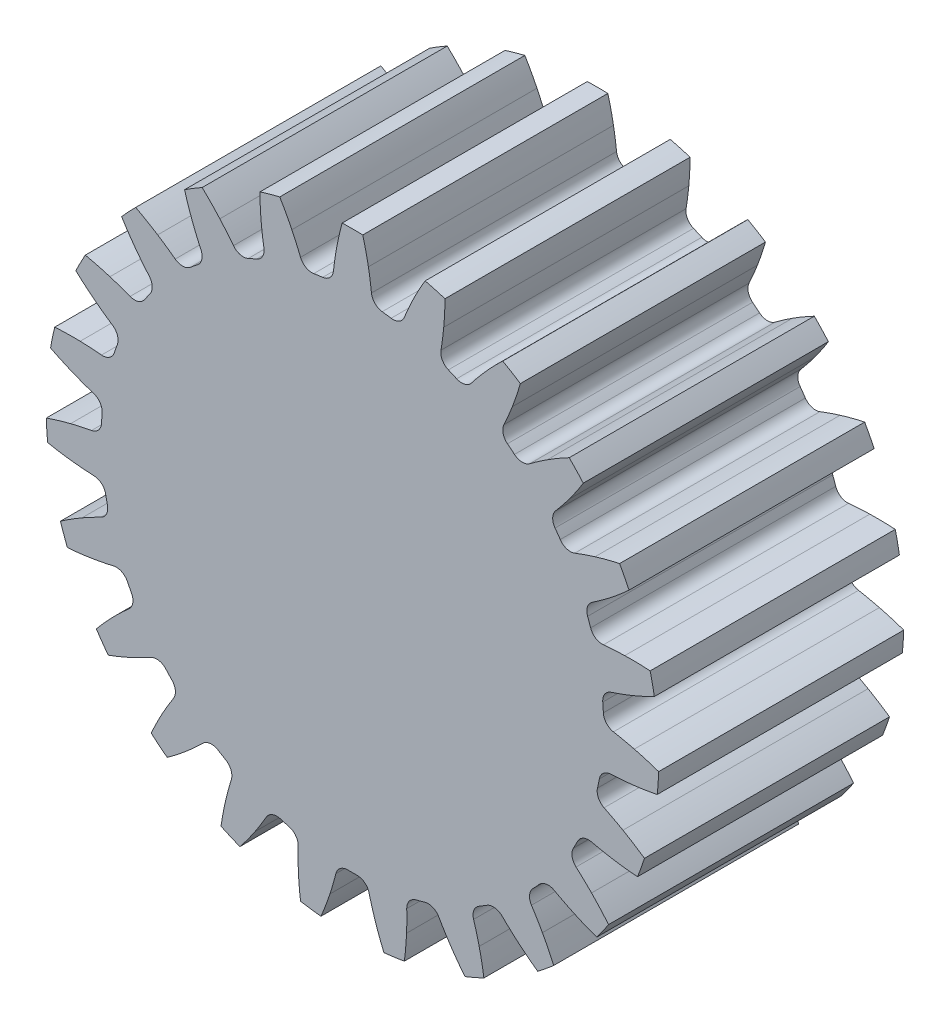
SolidWorks part; units mm, degrees
ref_plane "Front Plane" through (0, 0, 0) normal (0, 0, 1) x (1, 0, 0)
ref_plane "Top Plane" through (0, 0, 0) normal (0, 1, 0) x (1, 0, 0)
ref_plane "Right Plane" through (0, 0, 0) normal (1, 0, 0) x (0, 0, -1)
sketch "Sketch1" plane through (0, 0, 0) normal (0, 0, 1) x (1, 0, 0)
  line L0 (0, 62.5) -> (0, -62.5) construction
  circle A0 centre (0, 0) radius 57.5 construction
  circle A1 centre (0, 0) radius 62.5 construction
  arc A2 (-6.067, 50.8896) -> (-7.8878, 50.6394) centre (0, 0) ccw
  arc A3 (-2.1, 62.4647) -> (2.1, 62.4647) centre (0, 0) cw
  arc A4 (2.1, 62.4647) -> (3.25, 57.4081) centre (-53.7267, 47.1093) cw
  arc A5 (3.25, 57.4081) -> (3.8782, 53.0963) centre (-59.5523, 46.0563) cw
  arc A6 (3.8782, 53.0963) -> (6.067, 50.8896) centre (6.363, 53.372) ccw
  arc A7 (-3.8782, 53.0963) -> (-6.067, 50.8896) centre (-6.363, 53.372) cw
  arc A8 (-3.25, 57.4081) -> (-3.8782, 53.0963) centre (59.5523, 46.0563) ccw
  arc A9 (-2.1, 62.4647) -> (-3.25, 57.4081) centre (53.7267, 47.1093) ccw
  arc A10 (10.5908, 52.1736) -> (7.8878, 50.6394) centre (8.2726, 53.1096) cw
  arc A11 (12.359, 56.1561) -> (10.5908, 52.1736) centre (69.7698, 28.2814) ccw
  arc A12 (14.8307, 60.7149) -> (12.359, 56.1561) centre (64.4443, 30.8671) ccw
  arc A13 (14.8307, 60.7149) -> (18.8749, 59.5818) centre (0, 0) cw
  arc A14 (18.8749, 59.5818) -> (18.618, 54.4024) centre (-39.0244, 59.8576) cw
  arc A15 (18.618, 54.4024) -> (18.0596, 50.081) centre (-44.9181, 60.4154) cw
  arc A16 (18.0596, 50.081) -> (19.5719, 47.3656) centre (20.5266, 49.6762) ccw
  arc A17 (24.2743, 47.3815) -> (21.2577, 46.6334) centre (22.2946, 48.9082) cw
  arc A18 (27.0515, 50.7392) -> (24.2743, 47.3815) centre (74.8127, 8.409) ccw
  arc A19 (30.6614, 54.4622) -> (27.0515, 50.7392) centre (70.3824, 12.3356) ccw
  arc A20 (30.6614, 54.4622) -> (34.2499, 52.2799) centre (0, 0) cw
  arc A21 (34.2499, 52.2799) -> (32.6052, 47.3619) centre (-21.4279, 68.1666) cw
  arc A22 (32.6052, 47.3619) -> (30.9016, 43.3514) centre (-26.9525, 70.2938) cw
  arc A23 (30.9016, 43.3514) -> (31.6252, 40.3288) centre (33.1679, 42.296) ccw
  arc A24 (36.1576, 39.0754) -> (33.0509, 39.1689) centre (34.6632, 41.0795) cw
  arc A25 (39.7376, 41.5593) -> (36.1576, 39.0754) centre (74.3072, -12.0871) ccw
  arc A26 (44.2181, 44.1702) -> (39.7376, 41.5593) centre (71.1005, -7.1108) ccw
  arc A27 (44.2181, 44.1702) -> (47.0848, 41.1007) centre (0, 0) cw
  arc A28 (47.0848, 41.1007) -> (44.1742, 36.8088) centre (-2.2422, 71.42) cw
  arc A29 (44.1742, 36.8088) -> (41.4518, 33.4067) centre (-6.988, 74.9588) cw
  arc A30 (41.4518, 33.4067) -> (41.333, 30.3009) centre (43.3493, 31.779) ccw
  arc A31 (45.3592, 27.8712) -> (42.3929, 28.7993) centre (44.4609, 30.2042) cw
  arc A32 (49.4766, 29.2971) -> (45.3592, 27.8712) centre (68.2906, -31.6867) ccw
  arc A33 (54.4954, 30.6024) -> (49.4766, 29.2971) centre (66.5454, -26.0298) ccw
  arc A34 (54.4954, 30.6024) -> (56.4276, 26.8733) centre (0, 0) cw
  arc A35 (56.4276, 26.8733) -> (52.467, 23.5258) centre (17.1099, 69.3765) cw
  arc A36 (52.467, 23.5258) -> (48.9276, 20.9843) centre (13.4948, 74.0645) cw
  arc A37 (48.9276, 20.9843) -> (47.9754, 18.0257) centre (50.3156, 18.905) ccw
  arc A38 (51.1967, 14.5999) -> (48.5909, 16.2939) centre (50.9611, 17.0887) cw
  arc A39 (55.5461, 14.862) -> (51.1967, 14.5999) centre (57.2092, -48.9363) ccw
  arc A40 (60.7309, 14.7649) -> (55.5461, 14.862) centre (57.055, -43.0183) ccw
  arc A41 (60.7309, 14.7649) -> (61.5855, 10.6527) centre (0, 0) cw
  arc A42 (61.5855, 10.6527) -> (56.8686, 8.498) centre (35.1929, 62.1876) cw
  arc A43 (56.8686, 8.498) -> (52.7748, 7.0057) centre (32.9767, 67.6771) cw
  arc A44 (52.7748, 7.0057) -> (51.0596, 4.4137) centre (53.5503, 4.629) ccw
  arc A45 (53.2371, 0.2458) -> (51.185, 2.58) centre (53.6818, 2.7059) cw
  arc A46 (57.496, -0.6752) -> (53.2371, 0.2458) centre (41.8849, -62.5565) ccw
  arc A47 (62.4624, -2.1676) -> (57.496, -0.6752) centre (43.333, -56.8163) ccw
  arc A48 (62.4624, -2.1676) -> (62.1758, -6.3578) centre (0, 0) cw
  arc A49 (62.1758, -6.3578) -> (57.0525, -7.1601) centre (50.6659, 50.3866) cw
  arc A50 (57.0525, -7.1601) -> (52.7078, -7.4926) centre (50.0129, 56.2705) cw
  arc A51 (52.7078, -7.4926) -> (50.357, -9.5257) centre (52.8134, -9.9904) ccw
  arc A52 (51.3293, -14.1266) -> (49.983, -11.3252) centre (52.4212, -11.8776) cw
  arc A53 (55.1817, -16.1624) -> (51.3293, -14.1266) centre (23.4542, -71.5371) ccw
  arc A54 (59.5613, -18.9394) -> (55.1817, -16.1624) centre (26.3973, -66.4005) ccw
  arc A55 (59.5613, -18.9394) -> (58.1548, -22.8969) centre (0, 0) cw
  arc A56 (58.1548, -22.8969) -> (53.005, -22.2871) centre (62.3812, 34.8486) cw
  arc A57 (53.005, -22.2871) -> (48.7318, -21.4352) centre (63.3399, 40.6905) cw
  arc A58 (48.7318, -21.4352) -> (45.9196, -22.7586) centre (48.1596, -23.8688) ccw
  arc A59 (45.6145, -27.4512) -> (45.074, -24.3905) centre (47.2727, -25.5803) cw
  arc A60 (48.7749, -30.451) -> (45.6145, -27.4512) centre (3.284, -75.2122) ccw
  arc A61 (52.2428, -34.3065) -> (48.7749, -30.451) centre (7.5037, -71.0601) ccw
  arc A62 (52.2428, -34.3065) -> (49.8208, -37.7378) centre (0, 0) cw
  arc A63 (49.8208, -37.7378) -> (45.0265, -35.7613) centre (69.47, 16.7261) cw
  arc A64 (45.0265, -35.7613) -> (41.1416, -33.788) centre (71.9692, 22.0927) cw
  arc A65 (41.1416, -33.788) -> (38.0766, -34.3036) centre (39.934, -35.977) ccw
  arc A66 (36.5168, -38.7399) -> (36.8221, -35.6468) centre (38.6183, -37.3857) cw
  arc A67 (38.7506, -42.4811) -> (36.5168, -38.7399) centre (-17.1298, -73.3091) ccw
  arc A68 (41.0497, -47.1293) -> (38.7506, -42.4811) centre (-11.9463, -70.4495) ccw
  arc A69 (41.0497, -47.1293) -> (37.7917, -49.7799) centre (0, 0) cw
  arc A70 (37.7917, -49.7799) -> (33.7085, -46.5831) centre (71.4065, -2.6369) cw
  arc A71 (33.7085, -46.5831) -> (30.5, -43.6349) centre (75.261, 1.8564) cw
  arc A72 (30.5, -43.6349) -> (27.4096, -43.3045) centre (28.7466, -45.4169) ccw
  arc A73 (24.7108, -47.1554) -> (25.8392, -44.2594) centre (27.0997, -46.4184) cw
  arc A74 (25.8524, -51.3605) -> (24.7108, -47.1554) centre (-36.2732, -65.969) ccw
  arc A75 (26.8122, -56.4567) -> (25.8524, -51.3605) centre (-30.5103, -64.6139) ccw
  arc A76 (26.8122, -56.4567) -> (22.9599, -58.13) centre (0, 0) cw
  arc A77 (22.9599, -58.13) -> (19.8905, -53.9501) centre (68.0471, -21.8044) cw
  arc A78 (19.8905, -53.9501) -> (17.5965, -50.2456) centre (72.9709, -18.5176) cw
  arc A79 (17.5965, -50.2456) -> (14.7098, -49.0936) centre (15.4273, -51.4885) ccw
  arc A80 (11.072, -52.0736) -> (12.94, -49.5895) centre (13.5712, -52.0085) cw
  arc A81 (11.0368, -56.4308) -> (11.072, -52.0736) centre (-52.7263, -53.7363) ccw
  arc A82 (10.5861, -61.597) -> (11.0368, -56.4308) centre (-46.8116, -53.9863) ccw
  arc A83 (10.5861, -61.597) -> (6.4252, -62.1689) centre (0, 0) cw
  arc A84 (6.4252, -62.1689) -> (4.5973, -57.3159) centre (59.641, -39.3547) cw
  arc A85 (4.5973, -57.3159) -> (3.3878, -53.1298) centre (65.269, -37.5183) cw
  arc A86 (3.3878, -53.1298) -> (0.919, -51.2418) centre (0.9638, -53.7414) ccw
  arc A87 (-3.3878, -53.1298) -> (-0.919, -51.2418) centre (-0.9638, -53.7414) cw
  arc A88 (-4.5973, -57.3159) -> (-3.3878, -53.1298) centre (-65.269, -37.5183) ccw
  arc A89 (-6.4252, -62.1689) -> (-4.5973, -57.3159) centre (-59.641, -39.3547) ccw
  arc A90 (-6.4252, -62.1689) -> (-10.5861, -61.597) centre (0, 0) cw
  arc A91 (-10.5861, -61.597) -> (-11.0368, -56.4308) centre (46.8116, -53.9863) cw
  arc A92 (-11.0368, -56.4308) -> (-11.072, -52.0736) centre (52.7263, -53.7363) cw
  arc A93 (-11.072, -52.0736) -> (-12.94, -49.5895) centre (-13.5712, -52.0085) ccw
  arc A94 (-17.5965, -50.2456) -> (-14.7098, -49.0936) centre (-15.4273, -51.4885) cw
  arc A95 (-19.8905, -53.9501) -> (-17.5965, -50.2456) centre (-72.9709, -18.5176) ccw
  arc A96 (-22.9599, -58.13) -> (-19.8905, -53.9501) centre (-68.0471, -21.8044) ccw
  arc A97 (-22.9599, -58.13) -> (-26.8122, -56.4567) centre (0, 0) cw
  arc A98 (-26.8122, -56.4567) -> (-25.8524, -51.3605) centre (30.5103, -64.6139) cw
  arc A99 (-25.8524, -51.3605) -> (-24.7108, -47.1554) centre (36.2732, -65.969) cw
  arc A100 (-24.7108, -47.1554) -> (-25.8392, -44.2594) centre (-27.0997, -46.4184) ccw
  arc A101 (-30.5, -43.6349) -> (-27.4096, -43.3045) centre (-28.7466, -45.4169) cw
  arc A102 (-33.7085, -46.5831) -> (-30.5, -43.6349) centre (-75.261, 1.8564) ccw
  arc A103 (-37.7917, -49.7799) -> (-33.7085, -46.5831) centre (-71.4065, -2.6369) ccw
  arc A104 (-37.7917, -49.7799) -> (-41.0497, -47.1293) centre (0, 0) cw
  arc A105 (-41.0497, -47.1293) -> (-38.7506, -42.4811) centre (11.9463, -70.4495) cw
  arc A106 (-38.7506, -42.4811) -> (-36.5168, -38.7399) centre (17.1298, -73.3091) cw
  arc A107 (-36.5168, -38.7399) -> (-36.8221, -35.6468) centre (-38.6183, -37.3857) ccw
  arc A108 (-41.1416, -33.788) -> (-38.0766, -34.3036) centre (-39.934, -35.977) cw
  arc A109 (-45.0265, -35.7613) -> (-41.1416, -33.788) centre (-71.9692, 22.0927) ccw
  arc A110 (-49.8208, -37.7378) -> (-45.0265, -35.7613) centre (-69.47, 16.7261) ccw
  arc A111 (-49.8208, -37.7378) -> (-52.2428, -34.3065) centre (0, 0) cw
  arc A112 (-52.2428, -34.3065) -> (-48.7749, -30.451) centre (-7.5037, -71.0601) cw
  arc A113 (-48.7749, -30.451) -> (-45.6145, -27.4512) centre (-3.284, -75.2122) cw
  arc A114 (-45.6145, -27.4512) -> (-45.074, -24.3905) centre (-47.2727, -25.5803) ccw
  arc A115 (-48.7318, -21.4352) -> (-45.9196, -22.7586) centre (-48.1596, -23.8688) cw
  arc A116 (-53.005, -22.2871) -> (-48.7318, -21.4352) centre (-63.3399, 40.6905) ccw
  arc A117 (-58.1548, -22.8969) -> (-53.005, -22.2871) centre (-62.3812, 34.8486) ccw
  arc A118 (-58.1548, -22.8969) -> (-59.5613, -18.9394) centre (0, 0) cw
  arc A119 (-59.5613, -18.9394) -> (-55.1817, -16.1624) centre (-26.3973, -66.4005) cw
  arc A120 (-55.1817, -16.1624) -> (-51.3293, -14.1266) centre (-23.4542, -71.5371) cw
  arc A121 (-51.3293, -14.1266) -> (-49.983, -11.3252) centre (-52.4212, -11.8776) ccw
  arc A122 (-52.7078, -7.4926) -> (-50.357, -9.5257) centre (-52.8134, -9.9904) cw
  arc A123 (-57.0525, -7.1601) -> (-52.7078, -7.4926) centre (-50.0129, 56.2705) ccw
  arc A124 (-62.1758, -6.3578) -> (-57.0525, -7.1601) centre (-50.6659, 50.3866) ccw
  arc A125 (-62.1758, -6.3578) -> (-62.4624, -2.1676) centre (0, 0) cw
  arc A126 (-62.4624, -2.1676) -> (-57.496, -0.6752) centre (-43.333, -56.8163) cw
  arc A127 (-57.496, -0.6752) -> (-53.2371, 0.2458) centre (-41.8849, -62.5565) cw
  arc A128 (-53.2371, 0.2458) -> (-51.185, 2.58) centre (-53.6818, 2.7059) ccw
  arc A129 (-52.7748, 7.0057) -> (-51.0596, 4.4137) centre (-53.5503, 4.629) cw
  arc A130 (-56.8686, 8.498) -> (-52.7748, 7.0057) centre (-32.9767, 67.6771) ccw
  arc A131 (-61.5855, 10.6527) -> (-56.8686, 8.498) centre (-35.1929, 62.1876) ccw
  arc A132 (-61.5855, 10.6527) -> (-60.7309, 14.7649) centre (0, 0) cw
  arc A133 (-60.7309, 14.7649) -> (-55.5461, 14.862) centre (-57.055, -43.0183) cw
  arc A134 (-55.5461, 14.862) -> (-51.1967, 14.5999) centre (-57.2092, -48.9363) cw
  arc A135 (-51.1967, 14.5999) -> (-48.5909, 16.2939) centre (-50.9611, 17.0887) ccw
  arc A136 (-48.9276, 20.9843) -> (-47.9754, 18.0257) centre (-50.3156, 18.905) cw
  arc A137 (-52.467, 23.5258) -> (-48.9276, 20.9843) centre (-13.4948, 74.0645) ccw
  arc A138 (-56.4276, 26.8733) -> (-52.467, 23.5258) centre (-17.1099, 69.3765) ccw
  arc A139 (-56.4276, 26.8733) -> (-54.4954, 30.6024) centre (0, 0) cw
  arc A140 (-54.4954, 30.6024) -> (-49.4766, 29.2971) centre (-66.5454, -26.0298) cw
  arc A141 (-49.4766, 29.2971) -> (-45.3592, 27.8712) centre (-68.2906, -31.6867) cw
  arc A142 (-45.3592, 27.8712) -> (-42.3929, 28.7993) centre (-44.4609, 30.2042) ccw
  arc A143 (-41.4518, 33.4067) -> (-41.333, 30.3009) centre (-43.3493, 31.779) cw
  arc A144 (-44.1742, 36.8088) -> (-41.4518, 33.4067) centre (6.988, 74.9588) ccw
  arc A145 (-47.0848, 41.1007) -> (-44.1742, 36.8088) centre (2.2422, 71.42) ccw
  arc A146 (-47.0848, 41.1007) -> (-44.2181, 44.1702) centre (0, 0) cw
  arc A147 (-44.2181, 44.1702) -> (-39.7376, 41.5593) centre (-71.1005, -7.1108) cw
  arc A148 (-39.7376, 41.5593) -> (-36.1576, 39.0754) centre (-74.3072, -12.0871) cw
  arc A149 (-36.1576, 39.0754) -> (-33.0509, 39.1689) centre (-34.6632, 41.0795) ccw
  arc A150 (-30.9016, 43.3514) -> (-31.6252, 40.3288) centre (-33.1679, 42.296) cw
  arc A151 (-32.6052, 47.3619) -> (-30.9016, 43.3514) centre (26.9525, 70.2938) ccw
  arc A152 (-34.2499, 52.2799) -> (-32.6052, 47.3619) centre (21.4279, 68.1666) ccw
  arc A153 (-34.2499, 52.2799) -> (-30.6614, 54.4622) centre (0, 0) cw
  arc A154 (-30.6614, 54.4622) -> (-27.0515, 50.7392) centre (-70.3824, 12.3356) cw
  arc A155 (-27.0515, 50.7392) -> (-24.2743, 47.3815) centre (-74.8127, 8.409) cw
  arc A156 (-24.2743, 47.3815) -> (-21.2577, 46.6334) centre (-22.2946, 48.9082) ccw
  arc A157 (-18.0596, 50.081) -> (-19.5719, 47.3656) centre (-20.5266, 49.6762) cw
  arc A158 (-18.618, 54.4024) -> (-18.0596, 50.081) centre (44.9181, 60.4154) ccw
  arc A159 (-18.8749, 59.5818) -> (-18.618, 54.4024) centre (39.0244, 59.8576) ccw
  arc A160 (-18.8749, 59.5818) -> (-14.8307, 60.7149) centre (0, 0) cw
  arc A161 (-14.8307, 60.7149) -> (-12.359, 56.1561) centre (-64.4443, 30.8671) cw
  arc A162 (-12.359, 56.1561) -> (-10.5908, 52.1736) centre (-69.7698, 28.2814) cw
  arc A163 (-10.5908, 52.1736) -> (-7.8878, 50.6394) centre (-8.2726, 53.1096) ccw
  arc A164 (7.8878, 50.6394) -> (6.067, 50.8896) centre (0, 0) ccw
  arc A165 (21.2577, 46.6334) -> (19.5719, 47.3656) centre (0, 0) ccw
  arc A166 (33.0509, 39.1689) -> (31.6252, 40.3288) centre (0, 0) ccw
  arc A167 (42.3929, 28.7993) -> (41.333, 30.3009) centre (0, 0) ccw
  arc A168 (48.5909, 16.2939) -> (47.9754, 18.0257) centre (0, 0) ccw
  arc A169 (51.185, 2.58) -> (51.0596, 4.4137) centre (0, 0) ccw
  arc A170 (49.983, -11.3252) -> (50.357, -9.5257) centre (0, 0) ccw
  arc A171 (45.074, -24.3905) -> (45.9196, -22.7586) centre (0, 0) ccw
  arc A172 (36.8221, -35.6468) -> (38.0766, -34.3036) centre (0, 0) ccw
  arc A173 (25.8392, -44.2594) -> (27.4096, -43.3045) centre (0, 0) ccw
  arc A174 (12.94, -49.5895) -> (14.7098, -49.0936) centre (0, 0) ccw
  arc A175 (-0.919, -51.2418) -> (0.919, -51.2418) centre (0, 0) ccw
  arc A176 (-14.7098, -49.0936) -> (-12.94, -49.5895) centre (0, 0) ccw
  arc A177 (-27.4096, -43.3045) -> (-25.8392, -44.2594) centre (0, 0) ccw
  arc A178 (-38.0766, -34.3036) -> (-36.8221, -35.6468) centre (0, 0) ccw
  arc A179 (-45.9196, -22.7586) -> (-45.074, -24.3905) centre (0, 0) ccw
  arc A180 (-50.357, -9.5257) -> (-49.983, -11.3252) centre (0, 0) ccw
  arc A181 (-51.0596, 4.4137) -> (-51.185, 2.58) centre (0, 0) ccw
  arc A182 (-47.9754, 18.0257) -> (-48.5909, 16.2939) centre (0, 0) ccw
  arc A183 (-41.333, 30.3009) -> (-42.3929, 28.7993) centre (0, 0) ccw
  arc A184 (-31.6252, 40.3288) -> (-33.0509, 39.1689) centre (0, 0) ccw
  arc A185 (-19.5719, 47.3656) -> (-21.2577, 46.6334) centre (0, 0) ccw
  point P334 (0, 0)
  dimension "D1" = 115
  dimension "D2" = 125
  dimension "D3" = 102.5
  dimension "D5" = 2.5
  dimension "D6" = 63.82
  dimension "D7" = 57.9
  dimension "D4" = 3.25
  dimension "D8" = 2.1
  dimension "D9" = 23
extrude "Boss-Extrude1" add sketch "Sketch1" along normal blind 50
